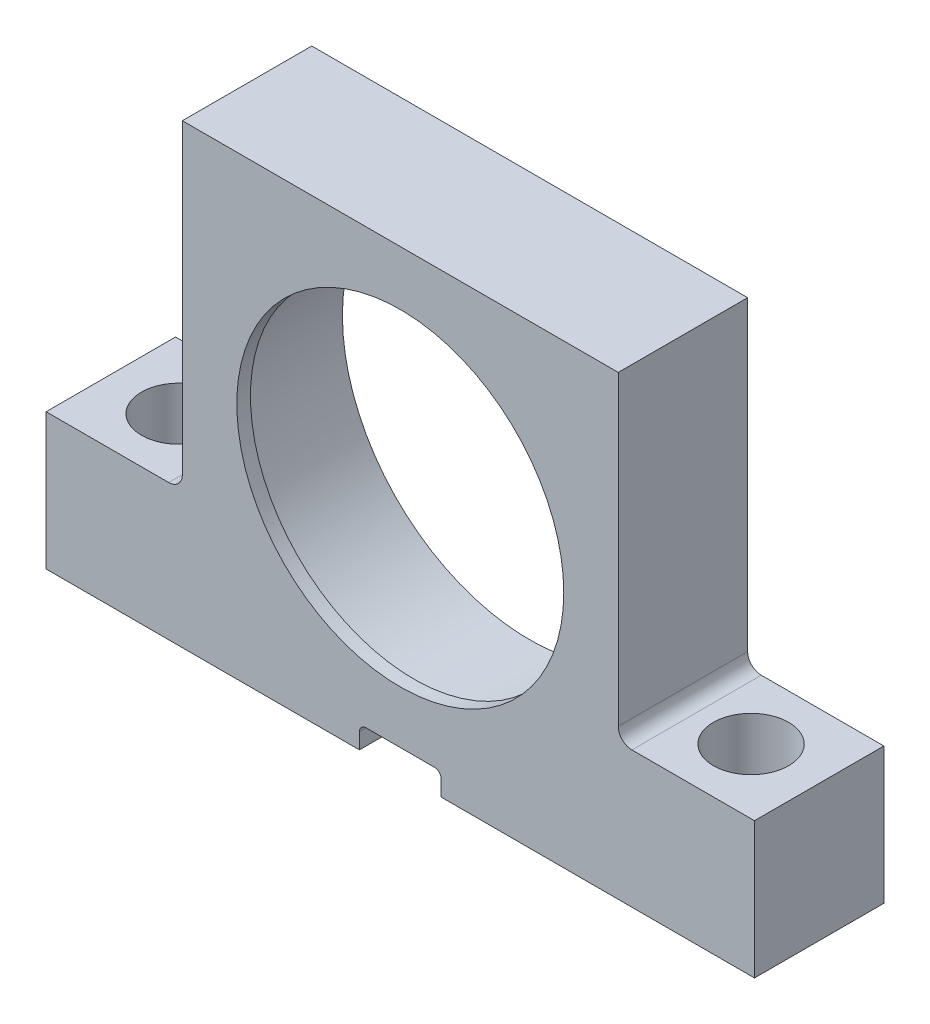
SolidWorks part; units mm, degrees
ref_plane "前视基准面" through (0, 0, 0) normal (0, 0, 1) x (1, 0, 0)
ref_plane "上视基准面" through (0, 0, 0) normal (0, 1, 0) x (1, 0, 0)
ref_plane "右视基准面" through (0, 0, 0) normal (1, 0, 0) x (0, 0, -1)
sketch "草图2" plane through (0, 0, 0) normal (0, 0, 1) x (1, 0, 0)
  line L0 (32, 10) -> (52, 10)
  line L1 (-52, 10) -> (-32, 10)
  line L2 (-52, 10) -> (-52, -10)
  line L3 (-52, -10) -> (52, -10)
  line L4 (52, 10) -> (52, -10)
  line L5 (0, -10) -> (0, 0) construction
  line L6 (-52, 0) -> (52, 0) construction
  line L8 (-32, 10) -> (-32, 57)
  line L9 (-32, 57) -> (32, 57)
  line L10 (32, 10) -> (32, 57)
  point P0 (0, 0)
  point P8 (0, 57)
  dimension "D1" = 104
  dimension "D2" = 20
  dimension "D3" = 64
  dimension "D4" = 47
extrude "凸台-拉伸1" add sketch "草图2" along normal blind 19
sketch "草图3" plane through (0, 0, 19) normal (0, 0, 1) x (1, 0, 0)
  line L0 (32, 57) -> (-32, 57) construction
  circle A0 centre (0, 25) radius 27.5
  point P4 (0, 0)
  dimension "D2" = 55
  dimension "D1" = 32
extrude "切除-拉伸1" cut sketch "草图3" against normal blind 19
sketch "草图4" plane through (0, 10, 0) normal (0, 1, 0) x (1, 0, 0)
  line L0 (-32, -19) -> (-32, 0) construction
  circle A0 centre (-42, -9.5) radius 5.5
  circle A1 centre (42, -9.5) radius 5.5233
  point P6 (-32, -9.5)
  point P7 (0, 0)
  dimension "D1" = 11
  dimension "D2" = 42
  dimension "D3" = 42
extrude "切除-拉伸2" cut sketch "草图4" against normal blind 30
sketch "草图5" plane through (0, 0, 19) normal (0, 0, 1) x (1, 0, 0)
  circle A0 centre (0, 25) radius 24
  circle A1 centre (0, 25) radius 27.5
  dimension "D1" = 48
extrude "凸台-拉伸2" add sketch "草图5" against normal blind 2
sketch "草图6" plane through (0, 0, 0) normal (0, 0, -1) x (-1, 0, 0)
  line L0 (52, -10) -> (-52, -10) construction
  line L1 (-6, -6.7) -> (6, -6.7)
  line L2 (-6, -6.7) -> (-6, -13.3)
  line L3 (-6, -13.3) -> (6, -13.3)
  line L4 (6, -6.7) -> (6, -13.3)
  line L5 (0, -13.3) -> (0, -6.7) construction
  line L6 (-6, -10) -> (6, -10) construction
  point P0 (0, -10)
  dimension "D1" = 12
  dimension "D2" = 6.6
extrude "切除-拉伸3" cut sketch "草图6" against normal blind 30
fillet "圆角1" radius 1 2 edges at (6, -6.7, 9.5) (-6, -6.7, 9.5)
fillet "圆角2" radius 2 2 edges at (-32, 10, 9.5) (32, 10, 9.5)
